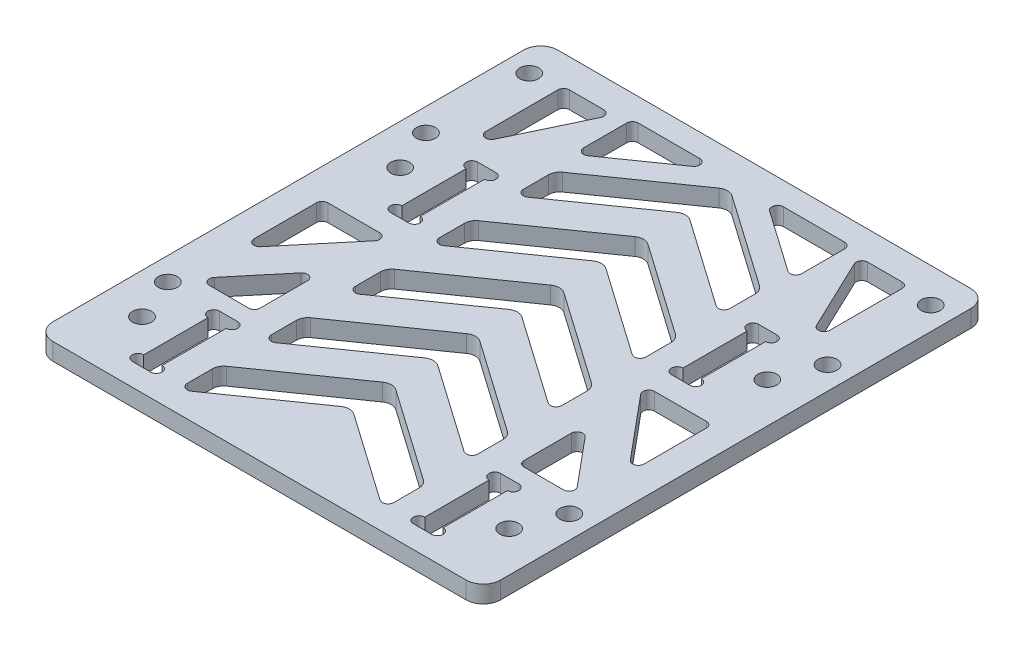
SolidWorks part; units mm, degrees
material "环氧树脂,未充填"
ref_plane "前视基准面" through (0, 0, 0) normal (0, 0, 1) x (1, 0, 0)
ref_plane "上视基准面" through (0, 0, 0) normal (0, 1, 0) x (1, 0, 0)
ref_plane "右视基准面" through (0, 0, 0) normal (1, 0, 0) x (0, 0, -1)
sketch "草图1" plane through (0, 0, 0) normal (0, 1, 0) x (1, 0, 0)
  line L0 (0, -1000) -> (0, 49000) construction
  line L1 (-32, -22.5) -> (32, -22.5) construction
  line L2 (-32, -22.5) -> (-32, 22.5) construction
  line L3 (-32, 22.5) -> (32, 22.5) construction
  line L4 (32, -22.5) -> (32, 22.5) construction
  line L5 (-32, -22.5) -> (32, 22.5) construction
  line L6 (-32, 22.5) -> (32, -22.5) construction
  line L7 (-1000, 0) -> (49000, 0) construction
  line L8 (-22.9, -959.1659) -> (-22.9, 49040.8341) construction
  line L9 (22.9, -955.0771) -> (22.9, 49044.9229) construction
  line L10 (-22.9, 63.8094) -> (22.9, 63.8094) construction
  line L11 (22.9, 14.9) -> (26.1, 14.9)
  line L12 (-22.9, 30.1) -> (-26.1, 30.1)
  line L13 (-22.9, 30.1) -> (-22.9, 14.9)
  line L14 (-22.9, 14.9) -> (-26.1, 14.9)
  line L15 (-26.1, 30.1) -> (-26.1, 14.9)
  line L16 (-22.9, 30.1) -> (-26.1, 14.9) construction
  line L17 (-22.9, 14.9) -> (-26.1, 30.1) construction
  line L18 (26.1, 30.1) -> (26.1, 14.9)
  line L19 (22.9, 30.1) -> (26.1, 30.1)
  line L20 (22.9, 30.1) -> (22.9, 14.9)
  line L21 (22.9, -30.1) -> (22.9, -14.9)
  line L22 (22.9, -30.1) -> (26.1, -30.1)
  line L23 (26.1, -30.1) -> (26.1, -14.9)
  line L24 (22.9, -14.9) -> (26.1, -14.9)
  line L25 (-22.9, -14.9) -> (-26.1, -14.9)
  line L26 (-26.1, -30.1) -> (-26.1, -14.9)
  line L27 (-22.9, -30.1) -> (-26.1, -30.1)
  line L28 (-22.9, -30.1) -> (-22.9, -14.9)
  line L29 (-35, 48) -> (35, 48) construction
  line L30 (-36, -34) -> (36, -34)
  line L31 (-39, -31) -> (-39, 51)
  line L32 (-36, 54) -> (36, 54)
  line L33 (39, -31) -> (39, 51)
  line L34 (-39, -34) -> (39, 54) construction
  line L35 (-39, 54) -> (39, -34) construction
  circle A0 centre (-32, 22.5) radius 1.65
  circle A1 centre (32, 22.5) radius 1.65
  circle A2 centre (32, -22.5) radius 1.65
  circle A3 centre (-32, -22.5) radius 1.65
  circle A4 centre (-35, 48) radius 1.65
  circle A5 centre (35, 48) radius 1.65
  circle A7 centre (-35, 30) radius 1.65
  circle A8 centre (35, 30) radius 1.65
  circle A9 centre (35, -15) radius 1.65
  circle A10 centre (-35, -15) radius 1.65
  arc A11 (-36, -34) -> (-39, -31) centre (-36, -31) cw
  arc A12 (36, -34) -> (39, -31) centre (36, -31) ccw
  arc A13 (36, 54) -> (39, 51) centre (36, 51) cw
  arc A14 (-39, 51) -> (-36, 54) centre (-36, 51) cw
  point P0 (0, 0)
  point P21 (0, 63.8094)
  point P26 (-24.5, 22.5)
  point P38 (0, 10)
  point P46 (0, 48)
  dimension "D3" = 3.3
  dimension "D12" = 3.3
  dimension "D17" = 45
  dimension "D18" = 3
  dimension "D1" = 64
  dimension "D2" = 45
  dimension "D4" = 45.8
  dimension "D5" = 14.9
  dimension "D6" = 15.2
  dimension "D7" = 3.2
  dimension "D8" = 10
  dimension "D9" = 88
  dimension "D10" = 78
  dimension "D11" = 70
  dimension "D14" = 18
  dimension "D15" = 48
  dimension "D13" = 2
  dimension "D16" = 2
extrude "凸台-拉伸1" add sketch "草图1" along normal blind 3
sketch "草图2" plane through (0, 3, 0) normal (0, 1, 0) x (1, 0, 0)
  line L0 (-22.9, -30.1) -> (-22.9, -14.9) construction
  line L1 (-26.1, -14.9) -> (-26.1, -30.1) construction
  line L2 (0, -1.65) -> (0, 1.65) construction
  line L3 (-1.65, 0) -> (1.65, 0) construction
  circle A0 centre (-22.9, -29.1) radius 1
  circle A1 centre (-26.1, -29.1) radius 1
  circle A2 centre (-22.9, -15.9) radius 1
  circle A3 centre (-26.1, -15.9) radius 1
  circle A4 centre (26.1, -15.9) radius 1
  circle A5 centre (22.9, -15.9) radius 1
  circle A6 centre (26.1, -29.1) radius 1
  circle A7 centre (22.9, -29.1) radius 1
  circle A8 centre (22.9, 29.1) radius 1
  circle A9 centre (26.1, 29.1) radius 1
  circle A10 centre (22.9, 15.9) radius 1
  circle A11 centre (26.1, 15.9) radius 1
  circle A12 centre (-26.1, 15.9) radius 1
  circle A13 centre (-22.9, 15.9) radius 1
  circle A14 centre (-26.1, 29.1) radius 1
  circle A15 centre (-22.9, 29.1) radius 1
  dimension "D1" = 2
extrude "切除-拉伸1" cut sketch "草图2" against normal blind 10
sketch "草图3" plane through (0, 0, 0) normal (0, -1, 0) x (1, 0, 0)
  line L1 (0, -1.65) -> (0, 1.65) construction
  line L38 (-30.865, 11.9) -> (-24, 11.9)
  line L39 (-23, 10.9) -> (-23, 2.662)
  line L40 (-24.7682, 2.0219) -> (-31.6332, 10.2598)
  line L41 (-32.2318, 1.6058) -> (-23.1771, -9.2598)
  line L42 (-23.9453, -10.9) -> (-33, -10.9)
  line L43 (-34, -9.9) -> (-34, 0.9657)
  line L44 (-39, -51) -> (-39, 31) construction
  line L45 (34, -9.9) -> (34, 0.9657)
  line L46 (-26.1, -14.9) -> (-22.9, -14.9) construction
  line L47 (23.9453, -10.9) -> (33, -10.9)
  line L48 (32.2318, 1.6058) -> (23.1771, -9.2598)
  line L49 (24.7682, 2.0219) -> (31.6332, 10.2598)
  line L50 (23, 10.9) -> (23, 2.662)
  line L51 (30.865, 11.9) -> (24, 11.9)
  line L52 (-28.0974, -34.9892) -> (-22.0974, -47.5695)
  line L53 (-23, -49) -> (-29, -49)
  line L54 (-30, -48) -> (-30, -35.4197)
  line L55 (36, -54) -> (-36, -54) construction
  line L56 (23, -49) -> (29, -49)
  line L57 (28.0974, -34.9892) -> (22.0974, -47.5695)
  line L58 (30, -48) -> (30, -35.4197)
  line L60 (-22.9, 14.9) -> (-26.1, 14.9) construction
  arc A30 (-32.2318, 1.6058) -> (-34, 0.9657) centre (-33, 0.9657) ccw
  arc A31 (-33, -10.9) -> (-34, -9.9) centre (-33, -9.9) cw
  arc A32 (-23.1771, -9.2598) -> (-23.9453, -10.9) centre (-23.9453, -9.9) cw
  arc A33 (-23, 2.662) -> (-24.7682, 2.0219) centre (-24, 2.662) cw
  arc A34 (-24, 11.9) -> (-23, 10.9) centre (-24, 10.9) cw
  arc A35 (-30.865, 11.9) -> (-31.6332, 10.2598) centre (-30.865, 10.9) ccw
  arc A36 (30.865, 11.9) -> (31.6332, 10.2598) centre (30.865, 10.9) cw
  arc A37 (24, 11.9) -> (23, 10.9) centre (24, 10.9) ccw
  arc A38 (23, 2.662) -> (24.7682, 2.0219) centre (24, 2.662) ccw
  arc A39 (23.1771, -9.2598) -> (23.9453, -10.9) centre (23.9453, -9.9) ccw
  arc A40 (33, -10.9) -> (34, -9.9) centre (33, -9.9) ccw
  arc A41 (32.2318, 1.6058) -> (34, 0.9657) centre (33, 0.9657) cw
  circle A42 centre (-35, -48) radius 1.65 construction
  arc A43 (-22.0974, -47.5695) -> (-23, -49) centre (-23, -48) cw
  arc A44 (-29, -49) -> (-30, -48) centre (-29, -48) cw
  arc A45 (-28.0974, -34.9892) -> (-30, -35.4197) centre (-29, -35.4197) ccw
  arc A46 (22.0974, -47.5695) -> (23, -49) centre (23, -48) ccw
  arc A47 (29, -49) -> (30, -48) centre (29, -48) ccw
  arc A48 (28.0974, -34.9892) -> (30, -35.4197) centre (29, -35.4197) cw
  point P119 (-23, -0.1)
  point P122 (-23, 11.9)
  point P125 (-33, 11.9)
  point P144 (33, 11.9)
  point P145 (23, 11.9)
  point P146 (23, -0.1)
  point P155 (-21.4152, -49)
  point P158 (-30, -49)
  point P161 (-30, -31)
  dimension "D20" = 1
  dimension "D25" = 1
  dimension "D3" = 23
  dimension "D4" = 3
  dimension "D5" = 23
  dimension "D14" = 6
  dimension "D16" = 5
  dimension "D17" = 4
  dimension "D18" = 10
  dimension "D19" = 12
  dimension "D21" = 5
  dimension "D22" = 5
  dimension "D24" = 18
extrude "切除-拉伸2" cut sketch "草图3" against normal blind 10
sketch "草图4" plane through (0, 0, 0) normal (0, 1, 0) x (-1, 0, 0)
  line L7 (0, 1.65) -> (0, -1.65) construction
  line L59 (-36, -54) -> (36, -54) construction
  line B0 (0, -48) -> (18, -35.3963)
  line B1 (18, -35.3963) -> (18, -28.0716)
  line B2 (18, -28.0716) -> (0, -40.6754)
  line B3 (0, -40.6754) -> (-18, -28.0716)
  line B4 (-18, -28.0716) -> (-18, -35.3963)
  line B5 (-18, -35.3963) -> (0, -48)
  line B6 (18, -50) -> (7.2891, -50)
  line B7 (6.7155, -48.1808) -> (17.4264, -40.681)
  line B8 (19, -41.5001) -> (19, -49)
  line B9 (-6.7155, -48.1808) -> (-17.4264, -40.681)
  line B10 (-18, -50) -> (-7.2891, -50)
  line B11 (-19, -41.5001) -> (-19, -49)
  line B12 (-17.1472, -21.3441) -> (-1.1472, -32.5475)
  line B13 (1.1472, -32.5475) -> (17.1472, -21.3441)
  line B14 (18, -19.7058) -> (18, -15.3433)
  line B15 (16.4264, -14.5242) -> (1.1472, -25.2228)
  line B16 (-1.1472, -25.2228) -> (-16.4264, -14.5242)
  line B17 (-18, -15.3433) -> (-18, -19.7058)
  line B18 (-17.1472, -6.6948) -> (-1.1472, -17.8982)
  line B19 (1.1472, -17.8982) -> (17.1472, -6.6948)
  line B20 (18, -5.0565) -> (18, -0.694)
  line B21 (16.4264, 0.1251) -> (1.1472, -10.5735)
  line B22 (-1.1472, -10.5735) -> (-16.4264, 0.1251)
  line B23 (-18, -0.694) -> (-18, -5.0565)
  line B24 (-17.1472, 7.9545) -> (-1.1472, -3.2489)
  line B25 (1.1472, -3.2489) -> (17.1472, 7.9545)
  line B26 (18, 9.5928) -> (18, 13.9553)
  line B27 (16.4264, 14.7744) -> (1.1472, 4.0758)
  line B28 (-1.1472, 4.0758) -> (-16.4264, 14.7744)
  line B29 (-18, 13.9553) -> (-18, 9.5928)
  line B30 (-17.1472, 22.6037) -> (-1.1472, 11.4004)
  line B31 (1.1472, 11.4004) -> (17.1472, 22.6037)
  line B32 (18, 24.2421) -> (18, 28.6046)
  line B33 (16.4264, 29.4237) -> (1.1472, 18.7251)
  line B34 (-1.1472, 18.7251) -> (-16.4264, 29.4237)
  line B35 (-18, 28.6046) -> (-18, 24.2421)
  arc B36 (7.2891, -50) -> (6.7155, -48.1808) centre (7.2891, -49) cw
  arc B37 (17.4264, -40.681) -> (19, -41.5001) centre (18, -41.5001) cw
  arc B38 (18, -50) -> (19, -49) centre (18, -49) ccw
  arc B39 (-7.2891, -50) -> (-6.7155, -48.1808) centre (-7.2891, -49) ccw
  arc B40 (-17.4264, -40.681) -> (-19, -41.5001) centre (-18, -41.5001) ccw
  arc B41 (-18, -50) -> (-19, -49) centre (-18, -49) cw
  arc B42 (17.1472, 22.6037) -> (18, 24.2421) centre (16, 24.2421) ccw
  arc B43 (-1.1472, 11.4004) -> (1.1472, 11.4004) centre (0, 13.0387) ccw
  arc B44 (-17.1472, 22.6037) -> (-18, 24.2421) centre (-16, 24.2421) cw
  arc B45 (-17.1472, 7.9545) -> (-18, 9.5928) centre (-16, 9.5928) cw
  arc B46 (-1.1472, -3.2489) -> (1.1472, -3.2489) centre (0, -1.6106) ccw
  arc B47 (17.1472, 7.9545) -> (18, 9.5928) centre (16, 9.5928) ccw
  arc B48 (17.1472, -6.6948) -> (18, -5.0565) centre (16, -5.0565) ccw
  arc B49 (-1.1472, -17.8982) -> (1.1472, -17.8982) centre (0, -16.2599) ccw
  arc B50 (-17.1472, -6.6948) -> (-18, -5.0565) centre (-16, -5.0565) cw
  arc B51 (-17.1472, -21.3441) -> (-18, -19.7058) centre (-16, -19.7058) cw
  arc B52 (17.1472, -21.3441) -> (18, -19.7058) centre (16, -19.7058) ccw
  arc B53 (-1.1472, -32.5475) -> (1.1472, -32.5475) centre (0, -30.9092) ccw
  arc B54 (-16.4264, -14.5242) -> (-18, -15.3433) centre (-17, -15.3433) ccw
  arc B55 (-16.4264, 0.1251) -> (-18, -0.694) centre (-17, -0.694) ccw
  arc B56 (-16.4264, 14.7744) -> (-18, 13.9553) centre (-17, 13.9553) ccw
  arc B57 (-16.4264, 29.4237) -> (-18, 28.6046) centre (-17, 28.6046) ccw
  arc B58 (18, 28.6046) -> (16.4264, 29.4237) centre (17, 28.6046) ccw
  arc B59 (18, 13.9553) -> (16.4264, 14.7744) centre (17, 13.9553) ccw
  arc B60 (18, -15.3433) -> (16.4264, -14.5242) centre (17, -15.3433) ccw
  arc B61 (18, -0.694) -> (16.4264, 0.1251) centre (17, -0.694) ccw
  arc B62 (1.1472, 18.7251) -> (-1.1472, 18.7251) centre (0, 20.3634) cw
  arc B63 (1.1472, 4.0758) -> (-1.1472, 4.0758) centre (0, 5.7141) cw
  arc B64 (1.1472, -10.5735) -> (-1.1472, -10.5735) centre (0, -8.9352) cw
  arc B65 (1.1472, -25.2228) -> (-1.1472, -25.2228) centre (0, -23.5845) cw
  dimension "D1" = 4
sketch_block_instance "块1-2"
sketch_block "块1" parameters "D4"=1, "D6"=2, "D7"=1, "D8"=2, "D1"=110, "D2"=6, "D3"=4, "D5"=6
extrude "切除-拉伸4" cut sketch "草图4" along normal blind 10
fillet "圆角3" radius 1 2 edges at (18, 1.5, -28.0716) (-18, 1.5, -28.0716)
fillet "圆角4" radius 2 4 edges at (-18, 1.5, -35.3963) (0, 1.5, -48) (18, 1.5, -35.3963) (0, 1.5, -40.6754)
